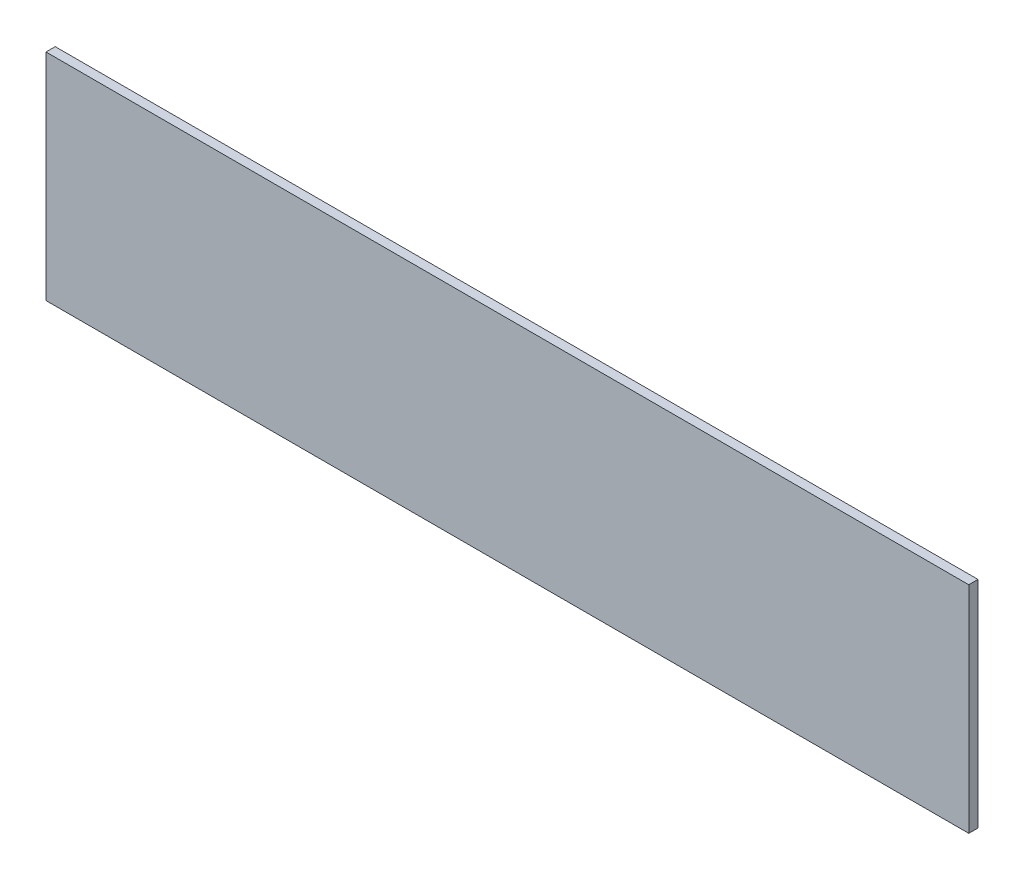
SolidWorks part; units mm, degrees
ref_plane "Спереди" through (0, 0, 0) normal (0, 0, 1) x (1, 0, 0)
ref_plane "Сверху" through (0, 0, 0) normal (0, 1, 0) x (1, 0, 0)
ref_plane "Справа" through (0, 0, 0) normal (1, 0, 0) x (0, 0, -1)
ref_plane "Плоскость4" through (0, 0, -10) normal (0, 0, 1) x (1, 0, 0)
sketch "Эскиз2" plane through (0, 0, -10) normal (0, 0, 1) x (1, 0, 0)
  line L1 (-150, -35) -> (150, -35)
  line L2 (-150, -35) -> (-150, 35)
  line L3 (-150, 35) -> (150, 35)
  line L4 (150, -35) -> (150, 35)
  line L5 (-150, -35) -> (150, 35) construction
  line L6 (-150, 35) -> (150, -35) construction
  point P0 (0, 0)
extrude "Бобышка-Вытянуть1" add sketch "Эскиз2" along normal blind 3
